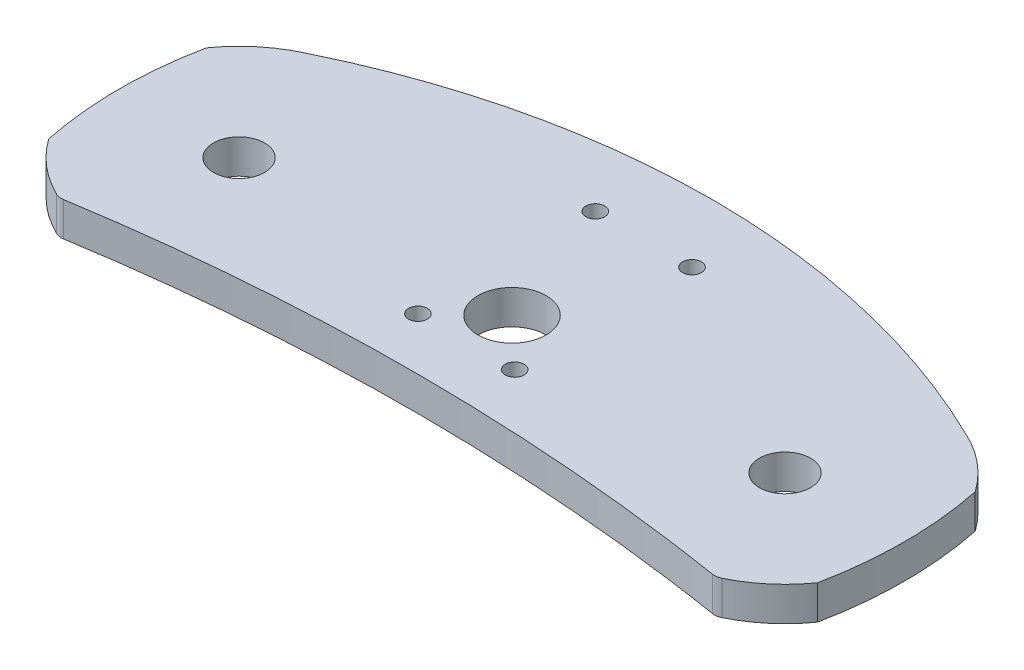
SolidWorks part; units mm, degrees
material "ABS"
ref_plane "Front Plane" through (0, 0, 0) normal (0, 0, 1) x (1, 0, 0)
ref_plane "Top Plane" through (0, 0, 0) normal (0, 1, 0) x (1, 0, 0)
ref_plane "Right Plane" through (0, 0, 0) normal (1, 0, 0) x (0, 0, -1)
sketch "Sketch1" plane through (0, 0, 0) normal (0, 1, 0) x (1, 0, 0)
  circle A0 centre (0, 0) radius 73.025
  dimension "D1" = 146.05
extrude "Boss-Extrude1" add sketch "Sketch1" along normal blind 6.35
sketch "Sketch2" plane through (0, 6.35, 0) normal (0, 1, 0) x (1, 0, 0)
  line L0 (0, -55) -> (0, 55) construction
  line L1 (-50.8, -25.4) -> (50.8, -25.4)
  line L3 (-50.8, 25.4) -> (50.8, 25.4)
  line L4 (71.842, -14.2265) -> (71.842, 14.2265)
  line L5 (-63.0049, -22.2756) -> (63.0049, 22.2756) construction
  line L6 (-63.0049, 22.2756) -> (63.0049, -22.2756) construction
  circle A0 centre (0, 0) radius 73.025 construction
  circle A1 centre (-50.8, 0) radius 4.7625
  circle A2 centre (50.8, 0) radius 4.7625
  circle A3 centre (-50.8, 0) radius 25.4
  circle A4 centre (50.8, 0) radius 25.4
  circle A5 centre (0, 0) radius 6.35
  arc A6 (-63.0049, 22.2756) -> (63.0049, 22.2756) centre (0, -102.4099) cw
  arc A7 (-63.0049, -22.2756) -> (63.0049, -22.2756) centre (0, 102.4099) ccw
  point P0 (0, 0)
  circle M2 centre (0, 0) radius 73.025
  dimension "D2" = 9.525
  dimension "D1" = 12.7
  dimension "D3" = 50.8
extrude "Cut-Extrude2" cut sketch "Sketch2" against normal blind 6.35 contours A4 A3 L3 M2 | A4 L1 A3 M2 | A1 | A2 | A5
sketch "Sketch3" plane through (0, 0, 0) normal (0, -1, 0) x (1, 0, 0)
  circle A0 centre (9, -24.5) radius 1.5 construction
  circle A1 centre (-9, -24.5) radius 1.5 construction
  circle A2 centre (9, 8.5) radius 1.5 construction
  circle A3 centre (-9, 8.5) radius 1.5 construction
  circle A4 centre (9, -24.5) radius 1.5
  circle A5 centre (-9, -24.5) radius 1.5
  circle A6 centre (9, 8.5) radius 1.5
  circle A7 centre (-9, 8.5) radius 1.5
  circle A8 centre (-9, 8.5) radius 1.75
  circle A9 centre (-9, -24.5) radius 1.75
  circle A10 centre (9, -24.5) radius 1.75
  circle A11 centre (9, 8.5) radius 1.75
  dimension "D1" = 3.5
  dimension "D2" = 3.5
  dimension "D3" = 3.5
  dimension "D4" = 3.5
extrude "Cut-Extrude3" cut sketch "Sketch3" against normal blind 10 contours A7 | A8 A7 | A5 | A9 A5 | A4 | A10 A4 | A6 | A11 A6
sketch "Sketch4" plane through (0, 6.35, 0) normal (0, 1, 0) x (1, 0, 0)
  line L0 (-6, 65) -> (-6, 31) construction
  line L1 (16, 31) -> (16, 65) construction
  line L2 (16, 65) -> (-6, 65) construction
  line L3 (-6, 65) -> (-6, 31)
  line L4 (16, 31) -> (16, 65)
  line L5 (16, 65) -> (-6, 65)
  line L6 (-16, -15) -> (16, -15)
  line L7 (16, -15) -> (16, 31)
  line L8 (16, 31) -> (9.7948, 31)
  line L9 (9.7948, 31) -> (0.2052, 31)
  line L10 (0.2052, 31) -> (-16, 31)
  line L11 (-16, 31) -> (-16, -15)
  line L12 (-16, -15) -> (16, -15)
  line L13 (16, -15) -> (16, 31)
  line L14 (16, 31) -> (9.7948, 31)
  line L15 (9.7948, 31) -> (0.2052, 31)
  line L16 (0.2052, 31) -> (-16, 31)
  line L17 (-16, 31) -> (-16, -15)
  dimension "D1" = 0
sketch "Sketch5" plane through (0, 6.35, 0) normal (0, 1, 0) x (1, 0, 0)
  arc A0 (-61.1508, -23.1953) -> (61.1508, -23.1953) centre (0, 102.4099) ccw construction
  arc A1 (-61.1508, -23.1953) -> (61.1508, -23.1953) centre (0, 102.4099) ccw
  spline S0 degree 2 poles (-61.1508, -23.1953) (0, -13.2848) (61.1508, -23.1953) knots 0 0 0 1 1 1
  dimension "D1" = 120.65
extrude "Cut-Extrude7" cut sketch "Sketch5" against normal through all
fillet "Fillet1" radius 2.54 2 edges at (61.1508, 3.175, 23.1953) (-61.1508, 3.175, 23.1953)
